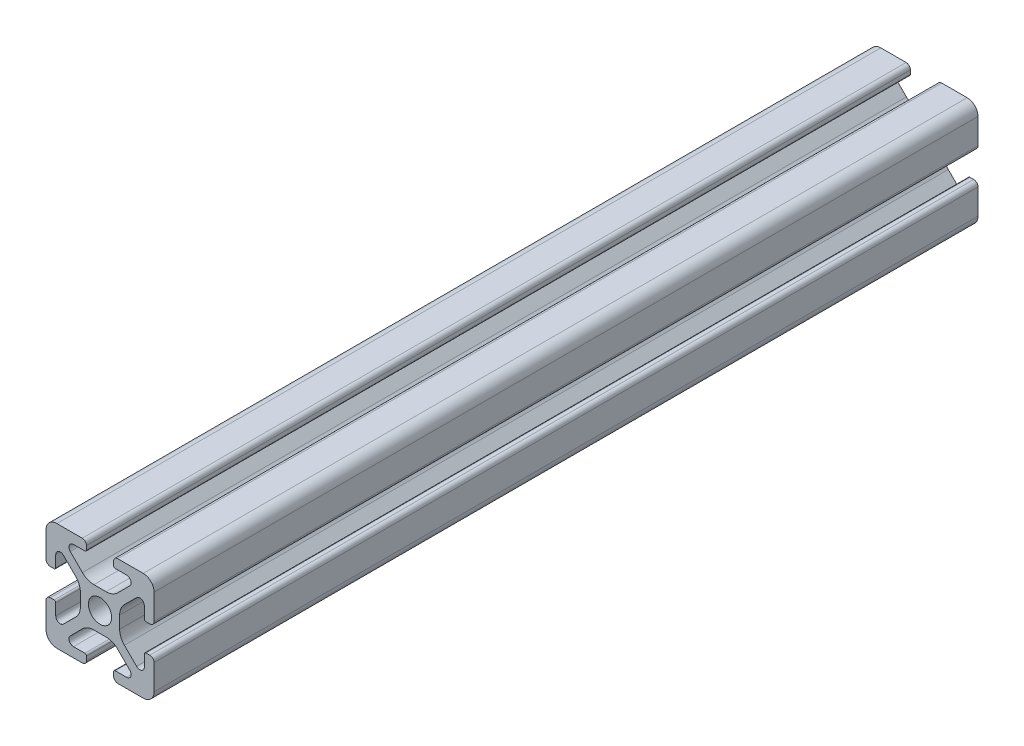
SolidWorks part; units mm, degrees
ref_plane "Front Plane" through (0, 0, 0) normal (0, 0, 1) x (1, 0, 0)
ref_plane "Top Plane" through (0, 0, 0) normal (0, 1, 0) x (1, 0, 0)
ref_plane "Right Plane" through (0, 0, 0) normal (1, 0, 0) x (0, 0, -1)
sketch "Sketch1" plane through (0, 0, 0) normal (0, 0, 1) x (1, 0, 0)
  line L2 (-9.9949, 7.9883) -> (-9.9949, 3.2893)
  line L3 (-7.9883, 9.9949) -> (-3.2893, 9.9949)
  line L4 (-2.5019, 9.2075) -> (-2.5019, 8.4963)
  line L5 (-2.8067, 8.1915) -> (-4.9149, 8.1915)
  line L6 (-5.5076, 6.7606) -> (-3.2528, 4.5058)
  line L7 (-6.7606, 5.5076) -> (-4.5058, 3.2528)
  line L8 (-8.1915, 4.9149) -> (-8.1915, 2.8067)
  line L9 (-8.4963, 2.5019) -> (-9.2075, 2.5019)
  line L11 (-1.1334, 3.6279) -> (1.1334, 3.6279)
  line L12 (-3.6279, 1.1334) -> (-3.6279, -1.1334)
  line L13 (8.4963, 2.5019) -> (9.2075, 2.5019)
  line L14 (8.1915, 4.9149) -> (8.1915, 2.8067)
  line L15 (9.9949, 7.9883) -> (9.9949, 3.2893)
  line L16 (7.9883, 9.9949) -> (3.2893, 9.9949)
  line L17 (2.5019, 9.2075) -> (2.5019, 8.4963)
  line L18 (2.8067, 8.1915) -> (4.9149, 8.1915)
  line L19 (3.6279, 1.1334) -> (3.6279, -1.1334)
  line L20 (5.5076, 6.7606) -> (3.2528, 4.5058)
  line L21 (6.7606, 5.5076) -> (4.5058, 3.2528)
  line L22 (-8.4963, -2.5019) -> (-9.2075, -2.5019)
  line L23 (-8.1915, -4.9149) -> (-8.1915, -2.8067)
  line L24 (-6.7606, -5.5076) -> (-4.5058, -3.2528)
  line L25 (-5.5076, -6.7606) -> (-3.2528, -4.5058)
  line L26 (-2.8067, -8.1915) -> (-4.9149, -8.1915)
  line L27 (-2.5019, -9.2075) -> (-2.5019, -8.4963)
  line L28 (-7.9883, -9.9949) -> (-3.2893, -9.9949)
  line L29 (-9.9949, -7.9883) -> (-9.9949, -3.2893)
  line L30 (9.9949, -7.9883) -> (9.9949, -3.2893)
  line L31 (7.9883, -9.9949) -> (3.2893, -9.9949)
  line L32 (2.5019, -9.2075) -> (2.5019, -8.4963)
  line L33 (2.8067, -8.1915) -> (4.9149, -8.1915)
  line L34 (5.5076, -6.7606) -> (3.2528, -4.5058)
  line L35 (6.7606, -5.5076) -> (4.5058, -3.2528)
  line L36 (8.1915, -4.9149) -> (8.1915, -2.8067)
  line L37 (8.4963, -2.5019) -> (9.2075, -2.5019)
  line L38 (-1.1334, -3.6279) -> (1.1334, -3.6279)
  circle A0 centre (0, 0) radius 2.1463
  arc A1 (-9.9949, 7.9883) -> (-7.9883, 9.9949) centre (-7.9883, 7.9883) cw
  arc A2 (-6.7606, 5.5076) -> (-8.1915, 4.9149) centre (-7.3533, 4.9149) ccw
  arc A3 (-4.9149, 8.1915) -> (-5.5076, 6.7606) centre (-4.9149, 7.3533) ccw
  arc A4 (-3.2893, 9.9949) -> (-2.5019, 9.2075) centre (-3.2893, 9.2075) cw
  arc A5 (-9.9949, 3.2893) -> (-9.2075, 2.5019) centre (-9.2075, 3.2893) ccw
  arc A6 (-8.1915, 2.8067) -> (-8.4963, 2.5019) centre (-8.4963, 2.8067) cw
  arc A7 (-2.5019, 8.4963) -> (-2.8067, 8.1915) centre (-2.8067, 8.4963) cw
  arc A8 (-1.1334, 3.6279) -> (-3.2528, 4.5058) centre (-1.1334, 6.6251) cw
  arc A9 (-3.6279, 1.1334) -> (-4.5058, 3.2528) centre (-6.6251, 1.1334) ccw
  arc A10 (8.1915, 2.8067) -> (8.4963, 2.5019) centre (8.4963, 2.8067) ccw
  arc A11 (9.9949, 3.2893) -> (9.2075, 2.5019) centre (9.2075, 3.2893) cw
  arc A12 (9.9949, 7.9883) -> (7.9883, 9.9949) centre (7.9883, 7.9883) ccw
  arc A13 (3.2893, 9.9949) -> (2.5019, 9.2075) centre (3.2893, 9.2075) ccw
  arc A14 (2.5019, 8.4963) -> (2.8067, 8.1915) centre (2.8067, 8.4963) ccw
  arc A15 (1.1334, 3.6279) -> (3.2528, 4.5058) centre (1.1334, 6.6251) ccw
  arc A16 (3.6279, 1.1334) -> (4.5058, 3.2528) centre (6.6251, 1.1334) cw
  arc A17 (6.7606, 5.5076) -> (8.1915, 4.9149) centre (7.3533, 4.9149) cw
  arc A18 (4.9149, 8.1915) -> (5.5076, 6.7606) centre (4.9149, 7.3533) cw
  arc A19 (-3.6279, -1.1334) -> (-4.5058, -3.2528) centre (-6.6251, -1.1334) cw
  arc A20 (-1.1334, -3.6279) -> (-3.2528, -4.5058) centre (-1.1334, -6.6251) ccw
  arc A21 (-2.5019, -8.4963) -> (-2.8067, -8.1915) centre (-2.8067, -8.4963) ccw
  arc A22 (-8.1915, -2.8067) -> (-8.4963, -2.5019) centre (-8.4963, -2.8067) ccw
  arc A23 (-9.9949, -3.2893) -> (-9.2075, -2.5019) centre (-9.2075, -3.2893) cw
  arc A24 (-3.2893, -9.9949) -> (-2.5019, -9.2075) centre (-3.2893, -9.2075) ccw
  arc A25 (-4.9149, -8.1915) -> (-5.5076, -6.7606) centre (-4.9149, -7.3533) cw
  arc A26 (-6.7606, -5.5076) -> (-8.1915, -4.9149) centre (-7.3533, -4.9149) cw
  arc A27 (-9.9949, -7.9883) -> (-7.9883, -9.9949) centre (-7.9883, -7.9883) ccw
  arc A28 (9.9949, -7.9883) -> (7.9883, -9.9949) centre (7.9883, -7.9883) cw
  arc A29 (6.7606, -5.5076) -> (8.1915, -4.9149) centre (7.3533, -4.9149) ccw
  arc A30 (4.9149, -8.1915) -> (5.5076, -6.7606) centre (4.9149, -7.3533) ccw
  arc A31 (3.2893, -9.9949) -> (2.5019, -9.2075) centre (3.2893, -9.2075) cw
  arc A32 (9.9949, -3.2893) -> (9.2075, -2.5019) centre (9.2075, -3.2893) ccw
  arc A33 (8.1915, -2.8067) -> (8.4963, -2.5019) centre (8.4963, -2.8067) cw
  arc A34 (2.5019, -8.4963) -> (2.8067, -8.1915) centre (2.8067, -8.4963) cw
  arc A35 (1.1334, -3.6279) -> (3.2528, -4.5058) centre (1.1334, -6.6251) cw
  arc A36 (3.6279, -1.1334) -> (4.5058, -3.2528) centre (6.6251, -1.1334) ccw
extrude "Boss-Extrude1" add sketch "Sketch1" along normal mid plane 152.4
